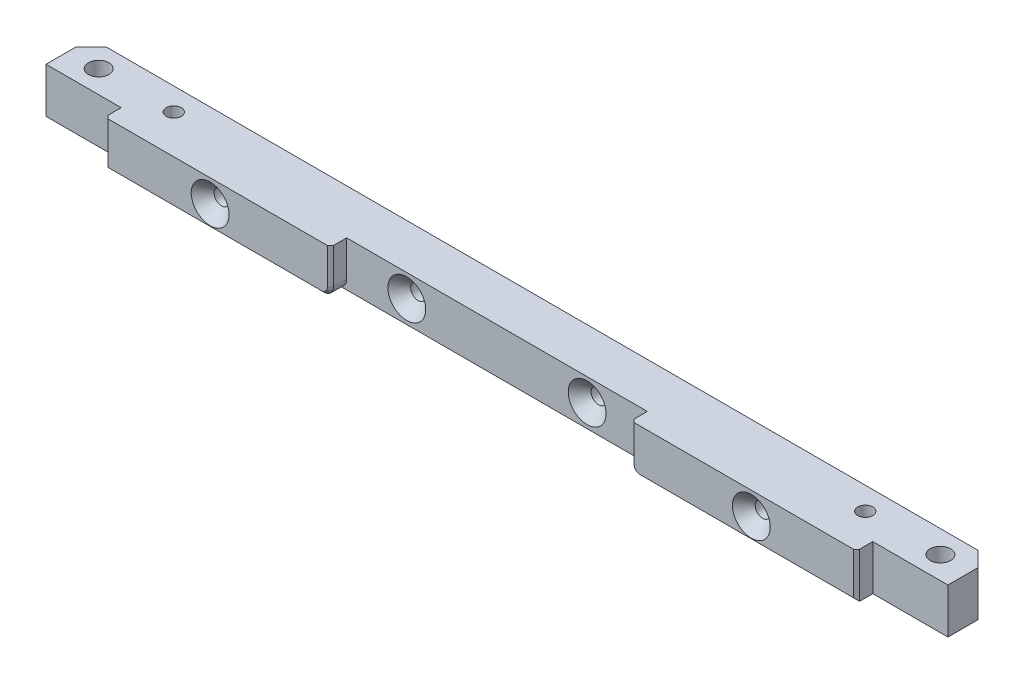
SolidWorks part; units mm, degrees
material "3.1355 (EN-AW 2024)"
ref_plane "Front" through (0, 0, 0) normal (0, 0, 1) x (1, 0, 0)
ref_plane "Top" through (0, 0, 0) normal (0, 1, 0) x (1, 0, 0)
ref_plane "Right" through (0, 0, 0) normal (1, 0, 0) x (0, 0, -1)
sketch "Эскиз1" plane through (0, 0, 0) normal (0, 1, 0) x (1, 0, 0)
  line L1 (-150, 7.5) -> (150, 7.5)
  line L2 (-150, 7.5) -> (-150, -7.5)
  line L3 (-150, -7.5) -> (150, -7.5)
  line L4 (150, 7.5) -> (150, -7.5)
  line L5 (-150, 7.5) -> (150, -7.5) construction
  line L6 (-150, -7.5) -> (150, 7.5) construction
  point P0 (0, 0)
  dimension "D1" = 300
  dimension "D2" = 15
extrude "База" add sketch "Эскиз1" along normal blind 15
hole_wizard "Крепление шарнира M6" positions "Эскиз2" profile "Эскиз3" tap size "M6" standard "DIN" end condition through all
sketch "Эскиз2" plane through (0, 15, 0) normal (0, 1, 0) x (1, 0, 0)
  line L6 (-115, 0) -> (0, 0) construction
  line L7 (0, 0) -> (115, 0) construction
  point P3 (-115, 0)
  point P5 (115, 0)
  dimension "D1" = 230
cosmetic thread "Отверстие резьбы12" parameters "D2"=6
cosmetic thread "Отверстие резьбы13" parameters "D2"=6
sketch "Эскиз3" plane through (-115, 15, 0) normal (1, 0, 0) x (0, 0, 1)
  line L0 (0, 0) -> (0, 15)
  line L1 (0, 15) -> (2.5, 15)
  line L2 (2.5, 15) -> (2.5, 0)
  line L5 (2.5, 0) -> (0, 0)
  line L11 (0, -6.35) -> (0, 107.95) construction
  dimension "Диаметр проходного сверла" = 5
  dimension "Глубина проходного сверла" = 15
hole_wizard "Шпилька-M8" positions "Эскиз6" profile "Эскиз7" tap size "M8" standard "DIN" end condition through all
sketch "Эскиз6" plane through (0, 15, 0) normal (0, 1, 0) x (1, 0, 0)
  line L2 (-140, 0) -> (-150, 0) construction
  line L3 (-150, 7.5) -> (-150, -7.5) construction
  line L8 (140, 0) -> (150, 0) construction
  line L9 (150, -7.5) -> (150, 7.5) construction
  point P0 (-140, 0)
  point P2 (140, 0)
  dimension "D1" = 10
cosmetic thread "Отверстие резьбы1" parameters "D2"=8
cosmetic thread "Отверстие резьбы2" parameters "D2"=8
sketch "Эскиз7" plane through (-140, 15, 0) normal (1, 0, 0) x (0, 0, 1)
  line L0 (0, 0) -> (0, 15)
  line L1 (0, 15) -> (3.4, 15)
  line L2 (3.4, 15) -> (3.4, 0)
  line L5 (3.4, 0) -> (0, 0)
  line L11 (0, -6.35) -> (0, 107.95) construction
  dimension "Диаметр проходного сверла" = 6.8
  dimension "Глубина проходного сверла" = 15
sketch "Эскиз8" plane through (0, 0, 7.5) normal (0, 0, 1) x (1, 0, 0)
  line L0 (-150, 15) -> (150, 15) construction
  line L1 (-125, 15) -> (125, 15)
  line L2 (-125, 15) -> (-125, 0)
  line L3 (-125, 0) -> (125, 0)
  line L4 (125, 15) -> (125, 0)
  line L5 (-150, 0) -> (150, 0) construction
  point P8 (0, 0)
  dimension "D1" = 250
extrude "Направляющая" add sketch "Эскиз8" along normal blind 5.4
sketch "Эскиз10" plane through (0, 0, 12.9) normal (0, 0, 1) x (1, 0, 0)
  line L0 (125, 15) -> (-125, 15) construction
  line L1 (-50, 15) -> (50, 15)
  line L2 (-50, 15) -> (-50, 0)
  line L3 (-50, 0) -> (50, 0)
  line L4 (50, 15) -> (50, 0)
  line L5 (-125, 0) -> (125, 0) construction
  point P8 (0, 15)
  dimension "D1" = 100
extrude "Вырез" cut sketch "Эскиз10" against normal blind 5.4
hole_wizard "Прижим-1-M6" positions "Эскиз4" profile "Эскиз5" tap size "M6" standard "DIN" end condition through all
sketch "Эскиз4" plane through (0, 0, 12.9) normal (0, 0, 1) x (1, 0, 0)
  line L23 (90, 7.5) -> (30, 7.5) construction
  line L24 (30, 7.5) -> (-30, 7.5) construction
  line L25 (-30, 7.5) -> (-90, 7.5) construction
  line L26 (0, 7.5) -> (0, 15) construction
  line L27 (150, 15) -> (-150, 15) construction
  line L30 (0, 7.5) -> (0, 0) construction
  point P4 (-90, 7.5)
  point P8 (90, 7.5)
  point P65 (0, 7.5)
  dimension "D1" = 180
sketch "Эскиз5" plane through (-90, 7.5, 12.9) normal (1, 0, 0) x (0, -1, 0)
  line L0 (0, 0) -> (0, 20.4)
  line L1 (0, 20.4) -> (2.5, 20.4)
  line L2 (2.5, 20.4) -> (2.5, 3.8)
  line L3 (2.5, 3.8) -> (6.3, 0)
  line L5 (6.3, 0) -> (0, 0)
  line L6 (-2.5, 3.8) -> (-6.3, 0) construction
  line L11 (0, -6.35) -> (0, 107.95) construction
  dimension "Диаметр проходного сверла" = 5
  dimension "Глубина проходного сверла" = 20.4
  dimension "Диаметр передней зенковки" = 12.6
  dimension "Угол передней зенковки" = 90
cosmetic thread "Отверстие резьбы16" parameters "D2"=6
cosmetic thread "Отверстие резьбы17" parameters "D2"=6
hole_wizard "Прижим-2-M6" positions "Эскиз11" profile "Эскиз12" tap size "M6" standard "ISO" end condition through all
sketch "Эскиз11" plane through (0, 0, 7.5) normal (0, 0, 1) x (1, 0, 0)
  line L0 (-30, 7.5) -> (0, 7.5) construction
  line L1 (0, 7.5) -> (30, 7.5) construction
  line L4 (0, 7.5) -> (0, 15) construction
  line L5 (50, 15) -> (-50, 15) construction
  line L8 (0, 7.5) -> (0, 0) construction
  point P0 (-30, 7.5)
  point P2 (30, 7.5)
  dimension "D1" = 60
sketch "Эскиз12" plane through (-30, 7.5, 7.5) normal (1, 0, 0) x (0, -1, 0)
  line L0 (0, 0) -> (0, 15)
  line L1 (0, 15) -> (2.5, 15)
  line L2 (2.5, 15) -> (2.5, 3.8)
  line L3 (2.5, 3.8) -> (6.3, 0)
  line L5 (6.3, 0) -> (0, 0)
  line L6 (-2.5, 3.8) -> (-6.3, 0) construction
  line L11 (0, -6.35) -> (0, 107.95) construction
  dimension "Диаметр проходного сверла" = 5
  dimension "Глубина проходного сверла" = 15
  dimension "Диаметр передней зенковки" = 12.6
  dimension "Угол передней зенковки" = 90
cosmetic thread "Отверстие резьбы20" parameters "D1"=0, "D2"=6
cosmetic thread "Отверстие резьбы21" parameters "D1"=0, "D2"=6
fillet "Скругление1" radius 3 2 edges at (50, 0, 10.2) (-50, 0, 10.2)
chamfer "Фаска1" distance 5 angle 45 2 edges at (150, 7.5, -7.5) (-150, 7.5, -7.5)
chamfer "Фаска2" distance 1 angle 45 8 edges at (125, 7.5, 12.9) (89, 0, 12.9) (50.8787, 0.8787, 12.9) (50, 9, 12.9) (-89, 0, 12.9) (-50.8787, 0.8787, 12.9) (-50, 9, 12.9) (-125, 7.5, 12.9)
